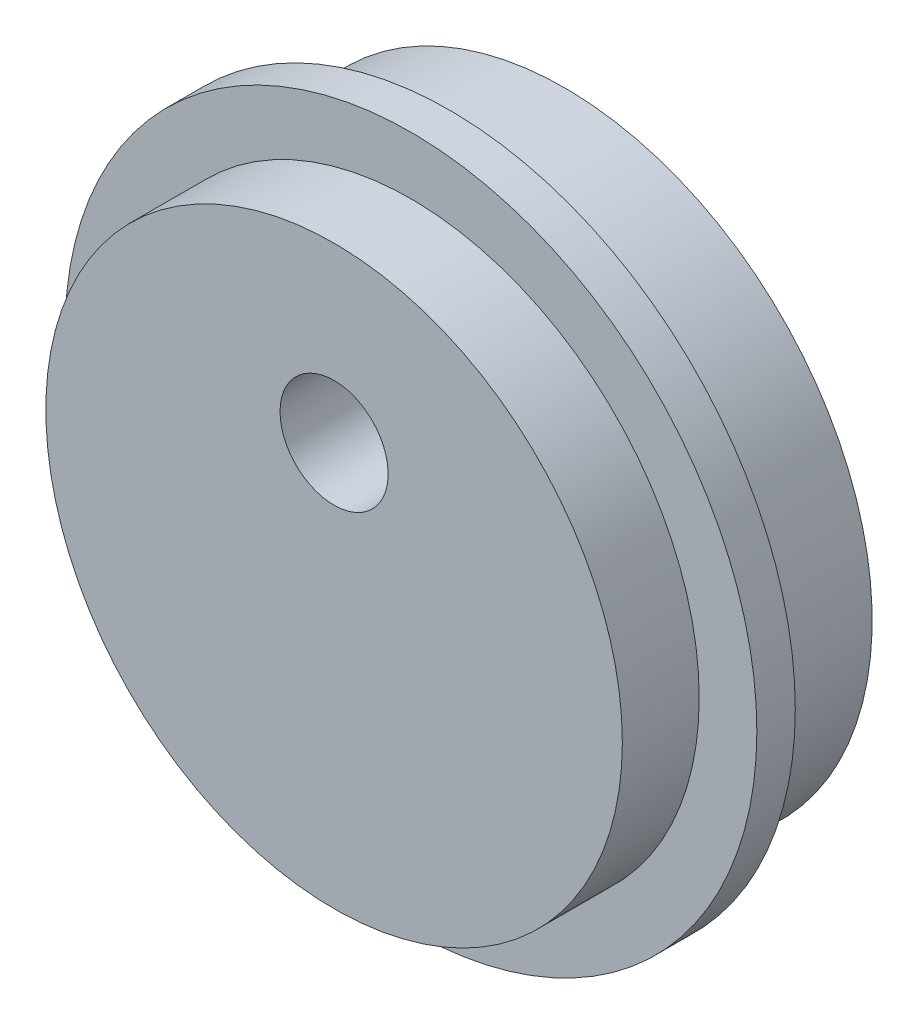
SolidWorks part; units mm, degrees
ref_plane "Front Plane" through (0, 0, 0) normal (0, 0, 1) x (1, 0, 0)
ref_plane "Top Plane" through (0, 0, 0) normal (0, 1, 0) x (1, 0, 0)
ref_plane "Right Plane" through (0, 0, 0) normal (1, 0, 0) x (0, 0, -1)
sketch "Sketch1" plane through (0, 0, 0) normal (0, 0, 1) x (1, 0, 0)
  circle A0 centre (0, 0) radius 50.8
  dimension "D1" = 101.6
extrude "Boss-Extrude1" add sketch "Sketch1" along normal blind 38.1
sketch "Sketch22" plane through (0, 0, 38.1) normal (0, 0, 1) x (1, 0, 0)
  circle A0 centre (0, 0) radius 47.625
  dimension "D1" = 95.25
extrude "Cut-Extrude-Thin2" cut sketch "Sketch22" against normal blind 12.7 thin
sketch "Sketch24" plane through (0, 0, 25.4) normal (0, 0, 1) x (1, 0, 0)
  circle A0 centre (0, 0) radius 57.15
extrude "Boss-Extrude3" add sketch "Sketch24" against normal blind 6.35
sketch "Sketch20" plane through (0, 0, 0) normal (0, 0, -1) x (-1, 0, 0)
  circle A0 centre (0, 19.05) radius 8.9297
  dimension "D1" = 17.8594
extrude "Cut-Extrude5" cut sketch "Sketch20" against normal through all and the other way through all
